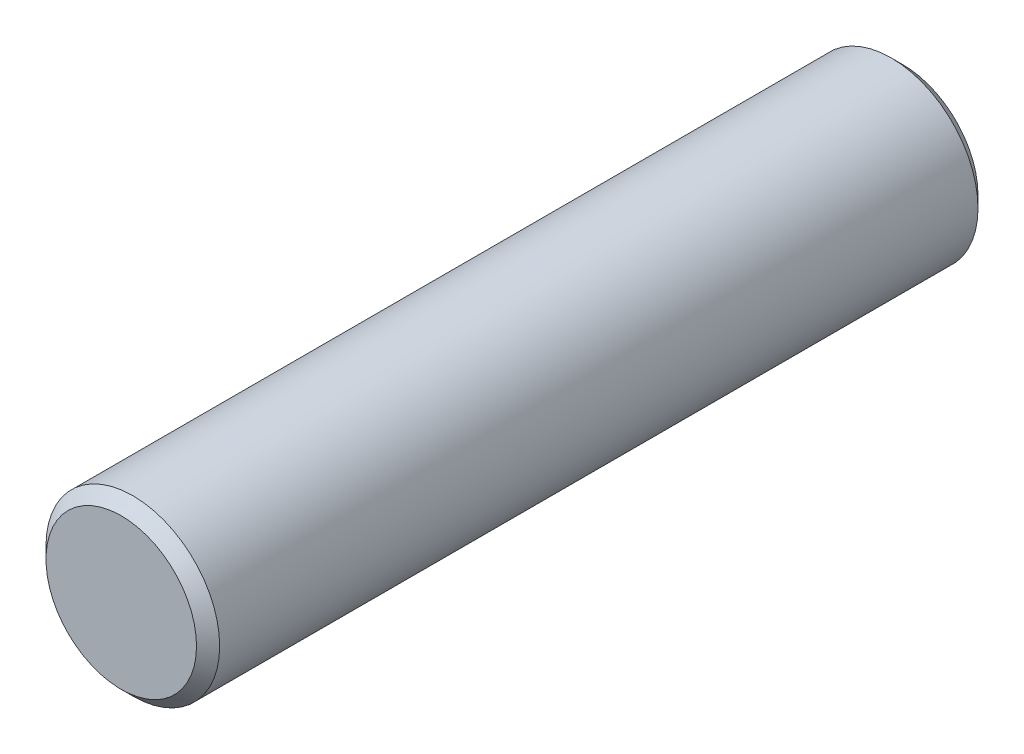
SolidWorks part; units mm, degrees
ref_plane "Front Plane" through (0, 0, 0) normal (0, 0, 1) x (1, 0, 0)
ref_plane "Top Plane" through (0, 0, 0) normal (0, 1, 0) x (1, 0, 0)
ref_plane "Right Plane" through (0, 0, 0) normal (1, 0, 0) x (0, 0, -1)
sketch "Sketch1" plane through (0, 0, 0) normal (0, 0, 1) x (1, 0, 0)
  circle A0 centre (0, 0) radius 1.5
  dimension "D1" = 3
extrude "Boss-Extrude2" add sketch "Sketch1" along normal blind 13.5 contours A0
chamfer "Chamfer1" distance 0.2 angle 45 1 edges at (1.5, 0, 13.5)
chamfer "Chamfer2" distance 0.2 angle 45 1 edges at (1.5, 0, 0)
